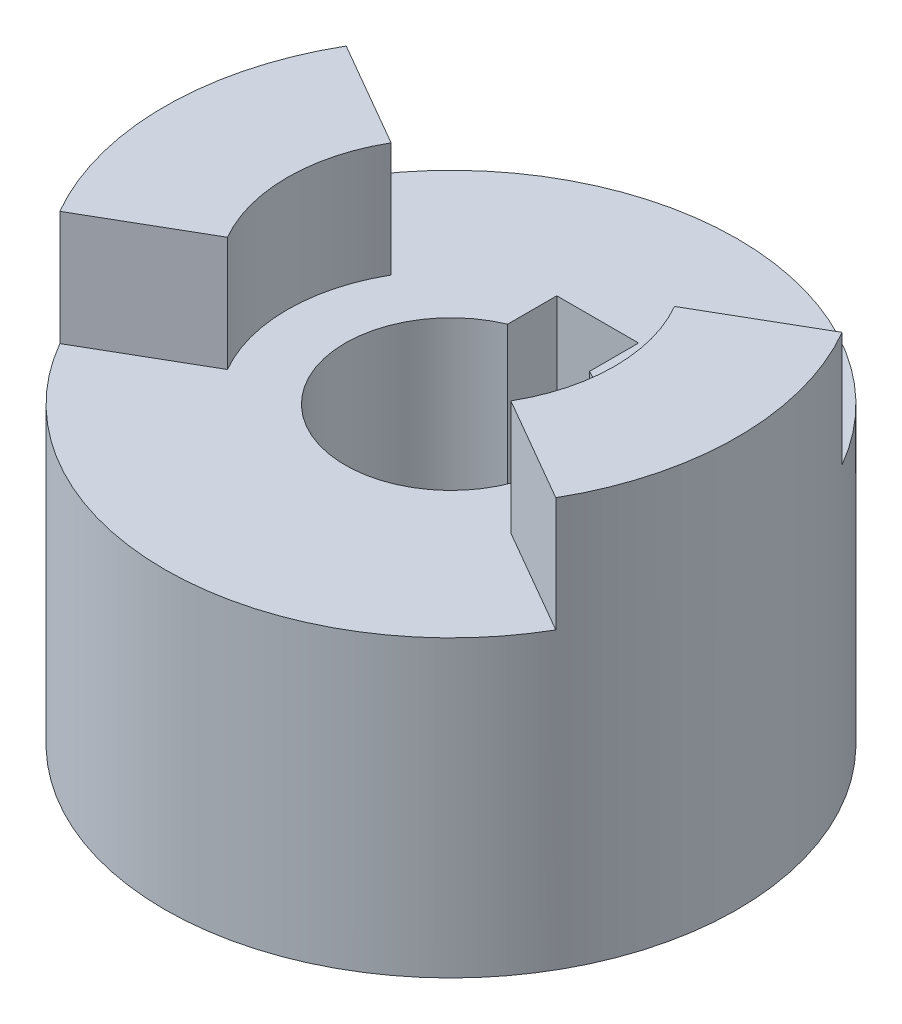
SolidWorks part; units mm, degrees
ref_plane "Front Plane" through (0, 0, 0) normal (0, 0, 1) x (1, 0, 0)
ref_plane "Top Plane" through (0, 0, 0) normal (0, 1, 0) x (1, 0, 0)
ref_plane "Right Plane" through (0, 0, 0) normal (1, 0, 0) x (0, 0, -1)
sketch "Sketch1" plane through (0, 0, 0) normal (0, 1, 0) x (1, 0, 0)
  circle A0 centre (0, 0) radius 35
  dimension "D1" = 70
extrude "Boss-Extrude1" add sketch "Sketch1" along normal blind 50
sketch "Sketch2" plane through (0, 50, 0) normal (0, 1, 0) x (1, 0, 0)
  line L1 (-10.3923, -6) -> (-30.3109, -17.5)
  line L8 (0, -27.5) -> (0, 27.5) construction
  line L9 (10.3923, -6) -> (30.3109, -17.5)
  arc A0 (-10.3923, -6) -> (10.3923, -6) centre (0, 0) ccw
  circle A2 centre (0, 0) radius 35 construction
  arc A3 (-30.3109, -17.5) -> (30.3109, -17.5) centre (0, 0) ccw
  dimension "D1" = 120
extrude "Cut-Extrude1" cut sketch "Sketch2" against normal offset from surface (14 mm away) 36 up to face at (0, 0, 35)
mirror "Mirror2" about plane through (0, 0, 0) normal (0, 0, 1) of "Cut-Extrude1"
sketch "Sketch3" plane through (0, 0, 0) normal (0, 1, 0) x (1, 0, 0)
  line L0 (5, 11.9241) -> (5, 17.93)
  line L1 (0, -27.5) -> (0, 27.5) construction
  line L2 (-5, 11.9241) -> (-5, 17.93)
  line L3 (5, 17.93) -> (-5, 17.93)
  line L4 (0, 12.93) -> (5, 12.93) construction
  arc A0 (-5, 11.9241) -> (5, 11.9241) centre (0, 0) ccw
  dimension "D1" = 25.86
  dimension "D2" = 10
  dimension "D3" = 5
extrude "Cut-Extrude2" cut sketch "Sketch3" along normal through all
sketch "Sketch4" plane through (0, 0, 0) normal (0, 1, 0) x (1, 0, 0)
  line L0 (5, 20) -> (5, 14.1421)
  line L1 (0, -27.5) -> (0, 27.5) construction
  line L2 (-5, 20) -> (-5, 14.1421)
  line L3 (5, 20) -> (-5, 20)
  line L4 (0, 15) -> (5, 15) construction
  arc A0 (-5, 14.1421) -> (5, 14.1421) centre (0, 0) ccw
  dimension "D1" = 30
  dimension "D2" = 10
  dimension "D3" = 5
extrude "Cut-Extrude3" [suppressed] cut sketch "Sketch4" along normal through all
sketch "Sketch5" plane through (0, 0, 0) normal (0, 1, 0) x (1, 0, 0)
  line L0 (5, 22.5) -> (5, 16.7705)
  line L1 (0, -27.5) -> (0, 27.5) construction
  line L2 (-5, 22.5) -> (-5, 16.7705)
  line L3 (5, 22.5) -> (-5, 22.5)
  line L4 (0, 17.5) -> (5, 17.5) construction
  arc A0 (-5, 16.7705) -> (5, 16.7705) centre (0, 0) ccw
  dimension "D1" = 35
  dimension "D2" = 10
  dimension "D3" = 5
extrude "Cut-Extrude4" [suppressed] cut sketch "Sketch5" along normal through all
sketch "Sketch7" [suppressed] plane through (0, 0, 0) normal (0, 1, 0) x (1, 0, 0)
  line L0 (0, -27.5) -> (0, 27.5) construction
  line L6 (5, -22.5) -> (-5, -22.5)
  line L7 (5, -22.5) -> (5, -12.5)
  line L8 (5, -12.5) -> (-5, -12.5)
  line L9 (-5, -22.5) -> (-5, -12.5)
  line L10 (5, -22.5) -> (-5, -12.5) construction
  line L11 (5, -12.5) -> (-5, -22.5) construction
  circle A0 centre (0, 0) radius 17.5 construction
  point P0 (0, -17.5)
  dimension "D1" = 10
extrude "Cut-Extrude6" [suppressed] cut sketch "Sketch7" along normal blind 40
sketch "Sketch10" plane through (0, 0, 0) normal (0, 1, 0) x (1, 0, 0)
  circle A0 centre (0, 0) radius 20
  dimension "D1" = 40
extrude "Cut-Extrude8" cut sketch "Sketch10" along normal through all from surface at 36 starting at face at (0, 36, -15.7693)
